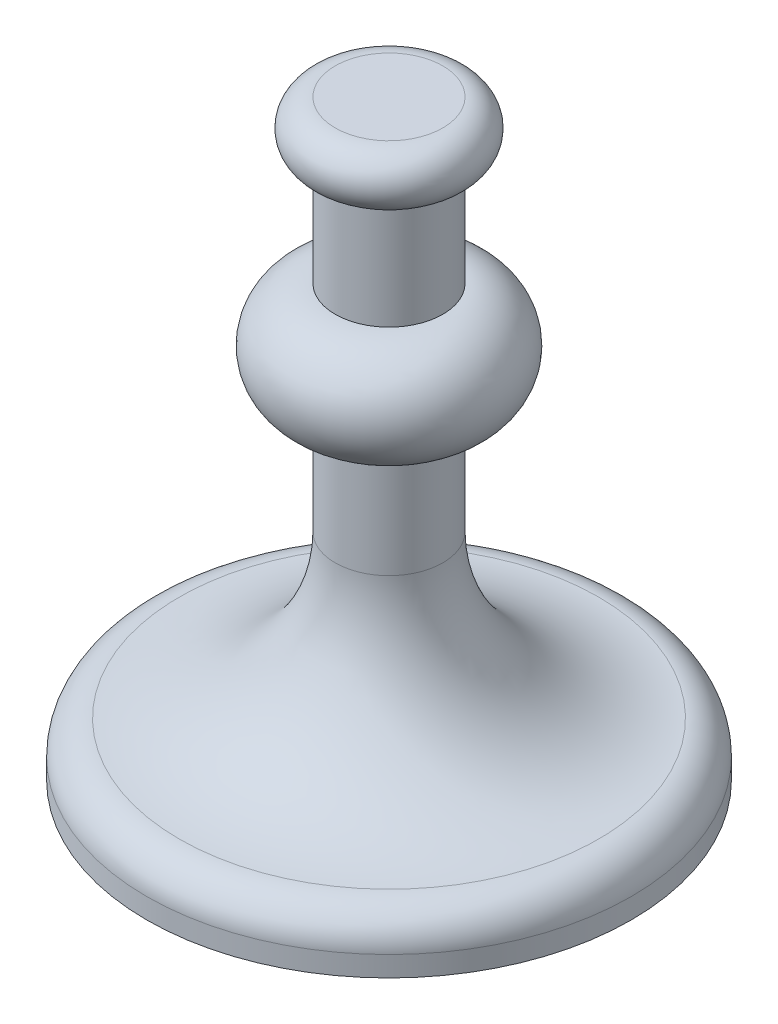
SolidWorks part; units mm, degrees
ref_plane "Front Plane" through (0, 0, 0) normal (0, 0, 1) x (1, 0, 0)
ref_plane "Top Plane" through (0, 0, 0) normal (0, 1, 0) x (1, 0, 0)
ref_plane "Right Plane" through (0, 0, 0) normal (1, 0, 0) x (0, 0, -1)
sketch "Sketch2" plane through (0, 0, 0) normal (0, 0, 1) x (1, 0, 0)
  line L0 (0, 110) -> (0, -110)
  line L1 (0, -110) -> (90, -110)
  line L2 (0, 110) -> (20, 110)
  line L3 (20, 90) -> (20, 50)
  line L5 (90, -102.4569) -> (90, -110)
  line L6 (20, 10.0016) -> (20, -30)
  arc A0 (20, 110) -> (20, 90) centre (20, 100) cw
  arc A1 (20, 50) -> (20, 10.0016) centre (20.18, 30.0008) cw
  arc A2 (77.931, -89.9643) -> (20, -30) centre (80, -30) cw
  arc A3 (90, -102.4569) -> (77.931, -89.9643) centre (77.5, -102.4569) ccw
  point P4 (0, 0)
  dimension "D4" = 10
  dimension "D5" = 20
  dimension "D8" = 60
  dimension "D7" = 12.5
  dimension "D1" = 220
  dimension "D2" = 20
  dimension "D3" = 90
  dimension "D6" = 40
revolve "Revolve1" add sketch "Sketch2" angle 360 about L0
